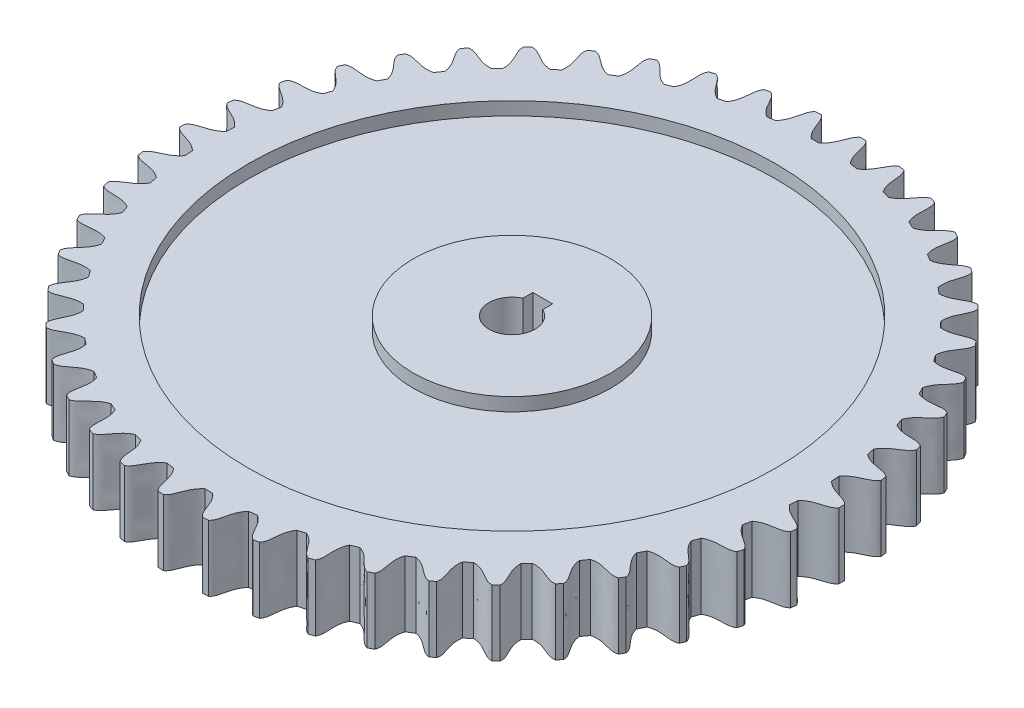
SolidWorks part; units mm, degrees
ref_plane "Plan de face" through (0, 0, 0) normal (0, 0, 1) x (1, 0, 0)
ref_plane "Plan de dessus" through (0, 0, 0) normal (0, 1, 0) x (1, 0, 0)
ref_plane "Plan de droite" through (0, 0, 0) normal (1, 0, 0) x (0, 0, -1)
sketch "Esquisse1" plane through (0, 0, 0) normal (0, 1, 0) x (1, 0, 0)
  line L1 (-1.5, 3.1623) -> (1.5, 3.1623) construction
  line L2 (-1.5, 3.1623) -> (-1.5, 4.6623)
  line L3 (-1.5, 4.6623) -> (1.5, 4.6623)
  line L4 (1.5, 4.6623) -> (1.5, 3.1623)
  circle A0 centre (0, 0) radius 50
  arc A1 (-1.5, 3.1623) -> (1.5, 3.1623) centre (0, 0) ccw
  circle A2 centre (0, 0) radius 48 construction
  dimension "D1" = 100
  dimension "D2" = 3
  dimension "D4" = 1.5
  dimension "D5" = 3.5
  dimension "D3" = 96
extrude "Boss.-Extru.2" add sketch "Esquisse1" along normal blind 10
sketch "Esquisse3" plane through (0, 10, 0) normal (0, 1, 0) x (1, 0, 0)
  line L0 (0, -13.5087) -> (0, 78.1714) construction
  line L1 (-0.6, 46) -> (0.6, 46)
  line L2 (-0.6, 46) -> (-2.1166, 47.3119) construction
  line L3 (-2.1166, 47.3119) -> (-1.8954, 49.1248) construction
  line L4 (-1.8954, 49.1248) -> (-2.9843, 49.9109) construction
  line L5 (0.6, 46) -> (2.1166, 47.3119) construction
  line L6 (2.1166, 47.3119) -> (1.8954, 49.1248) construction
  line L7 (1.8954, 49.1248) -> (2.9843, 49.9109) construction
  line L8 (0, 0) -> (0, 104.466) construction
  arc A0 (-2.9843, 49.9109) -> (2.9843, 49.9109) centre (0, 50) cw
  circle A1 centre (0, 0) radius 50 construction
  circle A5 centre (0, 0) radius 50 construction
  spline S0 degree 3 poles (-0.6, 46) (-2.1166, 47.3119) (-1.8954, 49.1248) (-2.9843, 49.9109) knots 0 0 0 0 1 1 1 1
  spline S1 degree 3 poles (0.6, 46) (2.1166, 47.3119) (1.8954, 49.1248) (2.9843, 49.9109) knots 0 0 0 0 1 1 1 1
  point P4 (0, 46)
  point P19 (0, 50)
  dimension "D2" = 1.2
  dimension "D7" = 4
extrude "Enlèv. mat.-Extru.2" cut sketch "Esquisse3" against normal blind 100
pattern_circular "Répétition circulaire3" count 46 every 7.826 about axis through (0, 10, 0) along (0, 1, 0) of "Enlèv. mat.-Extru.2"
sketch "Esquisse4" plane through (0, 10, 0) normal (0, 1, 0) x (1, 0, 0)
  circle A0 centre (0, 0) radius 15
  circle A1 centre (0, 0) radius 40
  dimension "D1" = 80
  dimension "D2" = 30
extrude "Enlèv. mat.-Extru.3" cut sketch "Esquisse4" against normal blind 2
sketch "Esquisse5" plane through (0, 0, 0) normal (0, -1, 0) x (1, 0, 0)
  circle A0 centre (0, 0) radius 15
  circle A1 centre (0, 0) radius 40
  dimension "D1" = 80
  dimension "D2" = 30
extrude "Enlèv. mat.-Extru.4" cut sketch "Esquisse5" against normal blind 2
